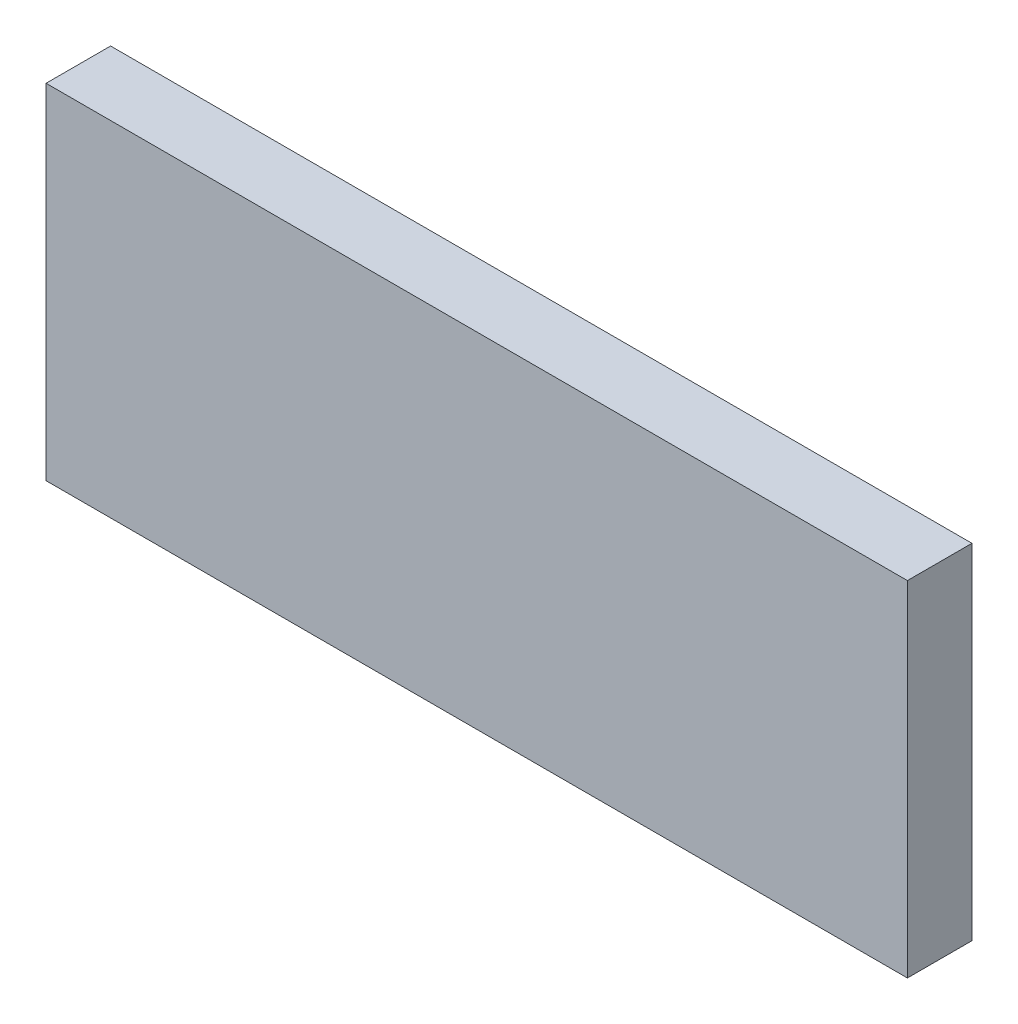
SolidWorks part; units mm, degrees
material "Cedro"
ref_plane "Alzado" through (0, 0, 0) normal (0, 0, 1) x (1, 0, 0)
ref_plane "Planta" through (0, 0, 0) normal (0, 1, 0) x (1, 0, 0)
ref_plane "Vista lateral" through (0, 0, 0) normal (1, 0, 0) x (0, 0, -1)
sketch "Croquis1" plane through (0, 0, 0) normal (1, 0, 0) x (0, 0, -1)
  line L1 (-7.5, -40) -> (7.5, -40)
  line L2 (-7.5, -40) -> (-7.5, 40)
  line L3 (-7.5, 40) -> (7.5, 40)
  line L4 (7.5, -40) -> (7.5, 40)
  line L5 (-7.5, -40) -> (7.5, 40) construction
  line L6 (-7.5, 40) -> (7.5, -40) construction
  point P0 (0, 0)
  dimension "D1" = 15
  dimension "D2" = 80
extrude "Saliente-Extruir1" add sketch "Croquis1" along normal blind 200.2
